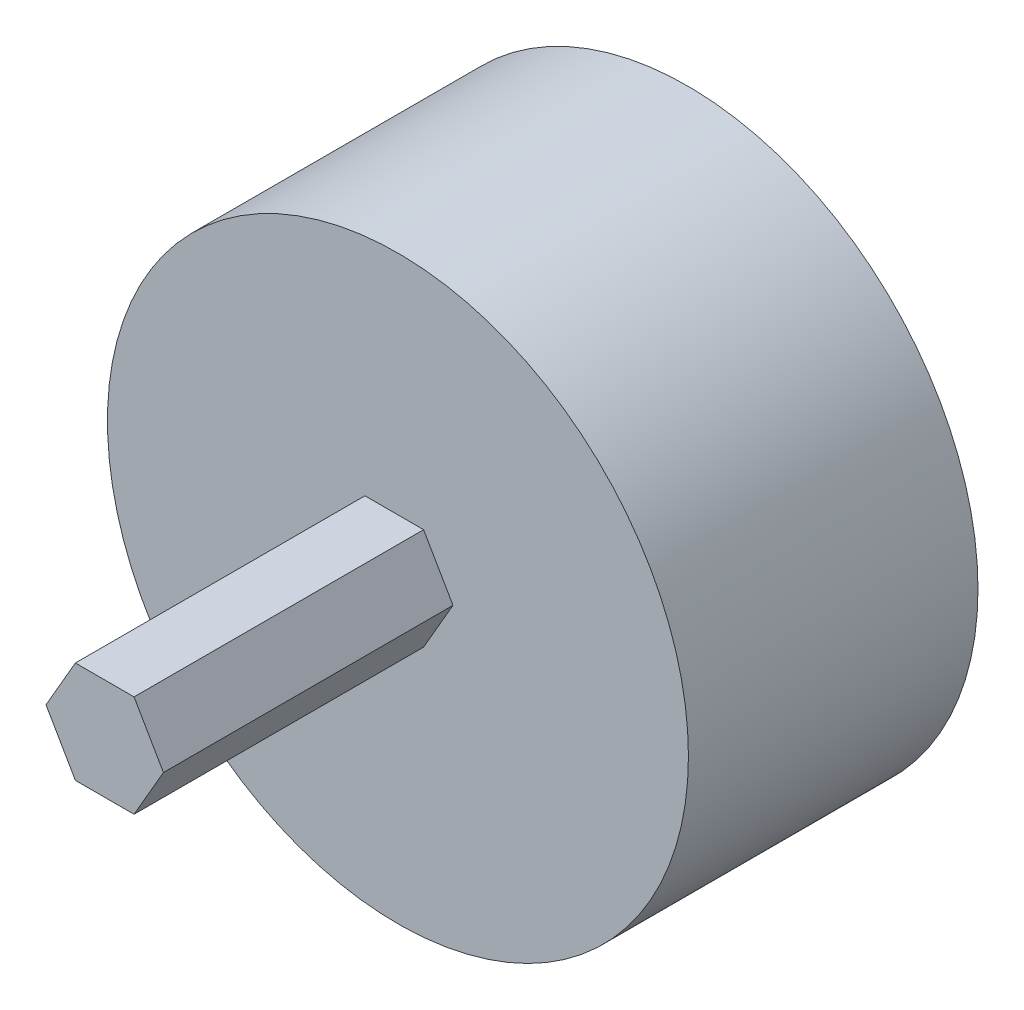
SolidWorks part; units mm, degrees
ref_plane "Front Plane" through (0, 0, 0) normal (0, 0, 1) x (1, 0, 0)
ref_plane "Top Plane" through (0, 0, 0) normal (0, 1, 0) x (1, 0, 0)
ref_plane "Right Plane" through (0, 0, 0) normal (1, 0, 0) x (0, 0, -1)
sketch "Sketch1" plane through (0, 0, 0) normal (0, 0, 1) x (1, 0, 0)
  circle A0 centre (-25.3845, 7.7523) radius 76.1919
extrude "Boss-Extrude1" add sketch "Sketch1" along normal blind 75.946
sketch "Sketch2" plane through (0, 0, 75.946) normal (0, 0, 1) x (1, 0, 0)
  line L1 (-10.9499, 11.1353) -> (-18.6489, 24.4703)
  line L2 (-18.6489, 24.4703) -> (-34.0468, 24.4703)
  line L3 (-34.0468, 24.4703) -> (-41.7458, 11.1353)
  line L4 (-41.7458, 11.1353) -> (-34.0468, -2.1997)
  line L5 (-34.0468, -2.1997) -> (-18.6489, -2.1997)
  line L6 (-18.6489, -2.1997) -> (-10.9499, 11.1353)
  circle A0 centre (-26.3478, 11.1353) radius 13.335 construction
  dimension "D1" = 26.67
extrude "Boss-Extrude2" add sketch "Sketch2" along normal blind 75.946
